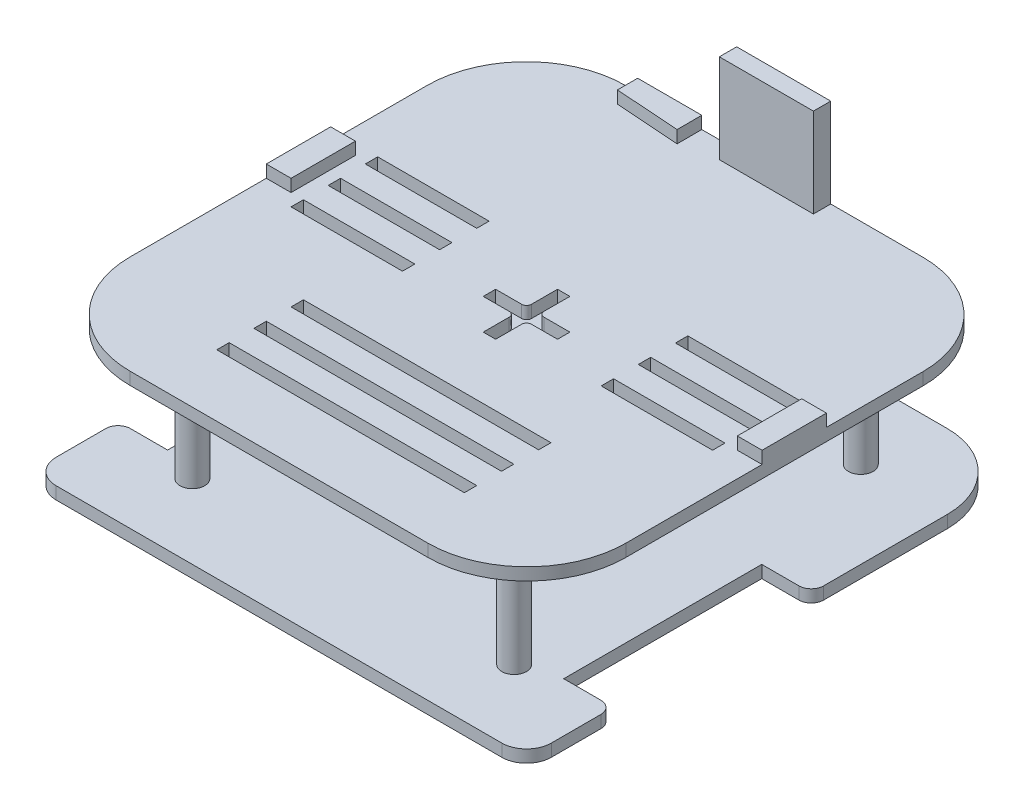
SolidWorks part; units mm, degrees
ref_plane "Front Plane" through (0, 0, 0) normal (0, 0, 1) x (1, 0, 0)
ref_plane "Top Plane" through (0, 0, 0) normal (0, 1, 0) x (1, 0, 0)
ref_plane "Right Plane" through (0, 0, 0) normal (1, 0, 0) x (0, 0, -1)
sketch "Sketch1" plane through (0, 0, 0) normal (0, 1, 0) x (1, 0, 0)
  line L1 (100, -100) -> (-100, -100)
  line L2 (100, -100) -> (100, 100)
  line L3 (100, 100) -> (-100, 100)
  line L4 (-100, -100) -> (-100, 100)
  line L5 (100, -100) -> (-100, 100) construction
  line L6 (100, 100) -> (-100, -100) construction
  point P0 (0, 0)
  dimension "D1" = 200
  dimension "D2" = 200
extrude "Boss-Extrude1" add sketch "Sketch1" along normal blind 5
fillet "Fillet1" radius 10 2 edges at (-100, 2.5, 100) (100, 2.5, 100)
fillet "Fillet3" radius 30 2 edges at (100, 2.5, -100) (-100, 2.5, -100)
sketch "Sketch5" plane through (0, 5, 0) normal (0, 1, 0) x (1, 0, 0)
  line L0 (-90, -100) -> (90, -100) construction
  line L1 (80, 15) -> (100, 15)
  line L2 (80, 15) -> (80, -65)
  line L3 (80, -65) -> (100, -65)
  line L4 (100, 15) -> (100, -65)
  line L5 (80, 15) -> (100, -65) construction
  line L6 (80, -65) -> (100, 15) construction
  line L7 (100, -90) -> (100, 70) construction
  point P0 (90, -25)
  dimension "D1" = 20
  dimension "D2" = 80
  dimension "D3" = 35
  dimension "D4" = 20
extrude "Cut-Extrude2" cut sketch "Sketch5" against normal through all
mirror "Mirror1" about plane through (0, 0, 0) normal (1, 0, 0) of "Cut-Extrude2"
sketch "Sketch8" plane through (0, 0, 0) normal (0, 0, 1) x (1, 0, 0)
  line L0 (-90, 5) -> (90, 5) construction
  line L1 (119.8679, 55) -> (-120.1321, 55)
  line L2 (119.8679, 55) -> (119.8679, 60)
  line L3 (119.8679, 60) -> (-120.1321, 60)
  line L4 (-120.1321, 55) -> (-120.1321, 60)
  line L5 (119.8679, 55) -> (-120.1321, 60) construction
  line L6 (119.8679, 60) -> (-120.1321, 55) construction
  point P0 (-0.1321, 57.5)
  dimension "D1" = 240
  dimension "D2" = 50
  dimension "D3" = 5
extrude "Boss-Extrude3" add sketch "Sketch8" along normal blind 100 and the other way blind 100 separate body
sketch "Sketch9" plane through (0, 0, 0) normal (0, 1, 0) x (1, 0, 0)
  circle A0 centre (-65, -70) radius 5
  dimension "D1" = 65
  dimension "D3" = 10
  dimension "D2" = 70
extrude "Boss-Extrude4" add sketch "Sketch9" along normal blind 58
mirror "Mirror5" about plane through (0, 0, 0) normal (1, 0, 0) of "Boss-Extrude4"
mirror "Mirror6" about plane through (0, 0, 0) normal (0, 0, 1) of "Mirror5", "Boss-Extrude4"
fillet "Fillet4" radius 5 4 edges at (-100, 2.5, -15) (100, 2.5, 65) (100, 2.5, -15) (-100, 2.5, 65)
sketch "Sketch11" plane through (0, 60, 0) normal (0, 1, 0) x (1, 0, 0)
  line L5 (2.5, -15) -> (-2.5, -15)
  line L6 (2.5, -15) -> (2.5, 15)
  line L7 (2.5, 15) -> (-2.5, 15)
  line L8 (-2.5, -15) -> (-2.5, 15)
  line L9 (2.5, -15) -> (-2.5, 15) construction
  line L10 (2.5, 15) -> (-2.5, -15) construction
  line L11 (15, -2.5) -> (-15, -2.5)
  line L12 (15, -2.5) -> (15, 2.5)
  line L13 (15, 2.5) -> (-15, 2.5)
  line L14 (-15, -2.5) -> (-15, 2.5)
  line L15 (15, -2.5) -> (-15, 2.5) construction
  line L16 (15, 2.5) -> (-15, -2.5) construction
  point P0 (0, 0)
  point P6 (0, 0)
  dimension "D1" = 30
  dimension "D2" = 5
  dimension "D3" = 30
  dimension "D4" = 5
extrude "Cut-Extrude4" cut sketch "Sketch11" against normal blind 5 contours L12 L13 L6 L11 | L6 L11 L8 L5 | L14 L11 L8 L13 | L13 L6 L7 L8 | L6 L13 L8 L11
fillet "Fillet6" radius 2 4 edges at (2.5, 57.5, 2.5) (-2.5, 57.5, 2.5) (2.5, 57.5, -2.5) (-2.5, 57.5, -2.5)
sketch "Sketch15" plane through (0, 60, 0) normal (0, 1, 0) x (1, 0, 0)
  line L0 (119.8679, -100) -> (-120.1321, -100) construction
  line L1 (49.8679, -40) -> (-50.1321, -40)
  line L2 (49.8679, -40) -> (49.8679, -45)
  line L3 (49.8679, -45) -> (-50.1321, -45)
  line L4 (-50.1321, -40) -> (-50.1321, -45)
  line L5 (49.8679, -40) -> (-50.1321, -45) construction
  line L6 (49.8679, -45) -> (-50.1321, -40) construction
  line L7 (49.8679, -55) -> (-50.1321, -55)
  line L8 (49.8679, -55) -> (49.8679, -60)
  line L9 (49.8679, -60) -> (-50.1321, -60)
  line L10 (-50.1321, -55) -> (-50.1321, -60)
  line L11 (49.8679, -55) -> (-50.1321, -60) construction
  line L12 (49.8679, -60) -> (-50.1321, -55) construction
  line L13 (49.8679, -75) -> (-50.1321, -75)
  line L14 (49.8679, -75) -> (49.8679, -70)
  line L15 (49.8679, -70) -> (-50.1321, -70)
  line L16 (-50.1321, -75) -> (-50.1321, -70)
  line L17 (49.8679, -75) -> (-50.1321, -70) construction
  line L18 (49.8679, -70) -> (-50.1321, -75) construction
  line L19 (119.8679, 100) -> (-120.1321, 100) construction
  line L20 (0, -2.75) -> (0, 2.75) construction
  line L21 (119.8679, 100) -> (119.8679, -100) construction
  line L22 (-120.1321, 100) -> (-120.1321, -100) construction
  line L23 (-85.1321, -10) -> (-40.1321, -10)
  line L24 (-85.1321, -10) -> (-85.1321, -5)
  line L25 (-85.1321, -5) -> (-40.1321, -5)
  line L26 (-40.1321, -10) -> (-40.1321, -5)
  line L27 (-85.1321, -10) -> (-40.1321, -5) construction
  line L28 (-85.1321, -5) -> (-40.1321, -10) construction
  line L29 (-40.1321, 5) -> (-85.1321, 5)
  line L30 (-40.1321, 5) -> (-40.1321, 10)
  line L31 (-40.1321, 10) -> (-85.1321, 10)
  line L32 (-85.1321, 5) -> (-85.1321, 10)
  line L33 (-40.1321, 5) -> (-85.1321, 10) construction
  line L34 (-40.1321, 10) -> (-85.1321, 5) construction
  line L35 (-40.1321, 20) -> (-85.1321, 20)
  line L36 (-40.1321, 20) -> (-40.1321, 25)
  line L37 (-40.1321, 25) -> (-85.1321, 25)
  line L38 (-85.1321, 20) -> (-85.1321, 25)
  line L39 (-40.1321, 20) -> (-85.1321, 25) construction
  line L40 (-40.1321, 25) -> (-85.1321, 20) construction
  line L41 (85.1321, -5) -> (40.1321, -5)
  line L42 (40.1321, -10) -> (40.1321, -5)
  line L43 (85.1321, -10) -> (40.1321, -10)
  line L44 (85.1321, -10) -> (85.1321, -5)
  line L45 (40.1321, 10) -> (85.1321, 10)
  line L46 (85.1321, 5) -> (85.1321, 10)
  line L47 (40.1321, 5) -> (85.1321, 5)
  line L48 (40.1321, 5) -> (40.1321, 10)
  line L49 (40.1321, 25) -> (85.1321, 25)
  line L50 (85.1321, 20) -> (85.1321, 25)
  line L51 (40.1321, 20) -> (85.1321, 20)
  line L52 (40.1321, 20) -> (40.1321, 25)
  point P0 (-0.1321, -42.5)
  point P5 (-0.1321, -57.5)
  point P10 (-0.1321, -72.5)
  point P19 (-85.1321, 7.5)
  point P20 (-62.6321, 7.5)
  point P21 (-62.6321, -7.5)
  point P30 (-62.6321, 22.5)
  dimension "D1" = 100
  dimension "D2" = 5
  dimension "D3" = 5
  dimension "D4" = 5
  dimension "D5" = 100
  dimension "D6" = 100
  dimension "D7" = 25
  dimension "D8" = 10
  dimension "D9" = 10
  dimension "D10" = 120
  dimension "D11" = 5
  dimension "D12" = 5
  dimension "D13" = 5
  dimension "D14" = 45
  dimension "D15" = 45
  dimension "D16" = 45
  dimension "D17" = 35
  dimension "D18" = 35
  dimension "D19" = 35
  dimension "D20" = 10
  dimension "D21" = 10
  dimension "D22" = 90
  dimension "D23" = 75
extrude "Cut-Extrude6" cut sketch "Sketch15" against normal blind 5
sketch "Sketch18" plane through (0, 60, 0) normal (0, 1, 0) x (1, 0, 0)
  line L0 (119.8679, -100) -> (-120.1321, -100) construction
  line L1 (-100.1321, -100) -> (-120.1321, -100)
  line L2 (-100.1321, -100) -> (-100.1321, 100)
  line L3 (-100.1321, 100) -> (-120.1321, 100)
  line L4 (-120.1321, -100) -> (-120.1321, 100)
  line L5 (-100.1321, -100) -> (-120.1321, 100) construction
  line L6 (-100.1321, 100) -> (-120.1321, -100) construction
  line L7 (-120.1321, 100) -> (-120.1321, -100) construction
  point P0 (-110.1321, 0)
  dimension "D1" = 200
  dimension "D2" = 20
  dimension "D3" = 0
extrude "Cut-Extrude7" cut sketch "Sketch18" against normal blind 5
mirror "Mirror7" about plane through (0, 0, 0) normal (1, 0, 0) of "Cut-Extrude7"
fillet "Fillet7" radius 40 4 edges at (100.1321, 57.5, -100) (100.1321, 57.5, 100) (-100.1321, 57.5, 100) (-100.1321, 57.5, -100)
sketch "Sketch22" plane through (0, 5, 0) normal (0, 1, 0) x (1, 0, 0)
  line L5 (16.2, -16) -> (22.2, -16)
  line L6 (16.2, -16) -> (16.2, -33)
  line L7 (16.2, -33) -> (22.2, -33)
  line L8 (22.2, -16) -> (22.2, -33)
  dimension "D1" = 16.2
  dimension "D2" = 16
  dimension "D3" = 17
  dimension "D4" = 6
extrude "Cut-Extrude10" cut sketch "Sketch22" against normal blind 5
mirror "Mirror8" about plane through (0, 0, 0) normal (1, 0, 0) of "Cut-Extrude10"
sketch "Sketch26" plane through (0, 60, 0) normal (0, 1, 0) x (1, 0, 0)
  line L0 (100.1321, -60) -> (100.1321, 60) construction
  line L1 (90.1321, 21) -> (100.1321, 21)
  line L2 (90.1321, 21) -> (90.1321, -5)
  line L3 (90.1321, -5) -> (100.1321, -5)
  line L4 (100.1321, 21) -> (100.1321, -5)
  line L7 (60.1321, -100) -> (-60.1321, -100) construction
  line L8 (-100.1321, 21) -> (-90.1321, 21)
  line L9 (-100.1321, 21) -> (-100.1321, -5)
  line L10 (-100.1321, -5) -> (-90.1321, -5)
  line L11 (-90.1321, 21) -> (-90.1321, -5)
  line L12 (-100.1321, -60) -> (-100.1321, 60) construction
  line L13 (-55.1321, 91.8345) -> (-55.1321, 100)
  line L14 (-55.1321, 91.8345) -> (-29.1969, 90.0001)
  line L15 (-29.1969, 90.0001) -> (-29.2429, 100)
  line L16 (-55.1321, 100) -> (-29.2429, 100)
  line L17 (60.1321, 100) -> (-60.1321, 100) construction
  dimension "D1" = 26
  dimension "D2" = 10
  dimension "D3" = 95
  dimension "D4" = 10
  dimension "D5" = 10
  dimension "D6" = 95
  dimension "D7" = 45
extrude "Boss-Extrude6" add sketch "Sketch26" along normal blind 5
sketch "Sketch27" plane through (0, 60, 0) normal (0, 1, 0) x (1, 0, 0)
  line L0 (60.1321, 100) -> (-29.2429, 100) construction
  line L1 (22.8679, 100) -> (-15.1321, 100)
  line L2 (22.8679, 100) -> (22.8679, 93)
  line L3 (22.8679, 93) -> (-15.1321, 93)
  line L4 (-15.1321, 100) -> (-15.1321, 93)
  line L5 (-100.1321, 21) -> (-100.1321, 60) construction
  point P6 (-15.1321, 96.5)
  dimension "D1" = 38
  dimension "D2" = 7
  dimension "D3" = 85
extrude "Boss-Extrude7" add sketch "Sketch27" along normal blind 36
